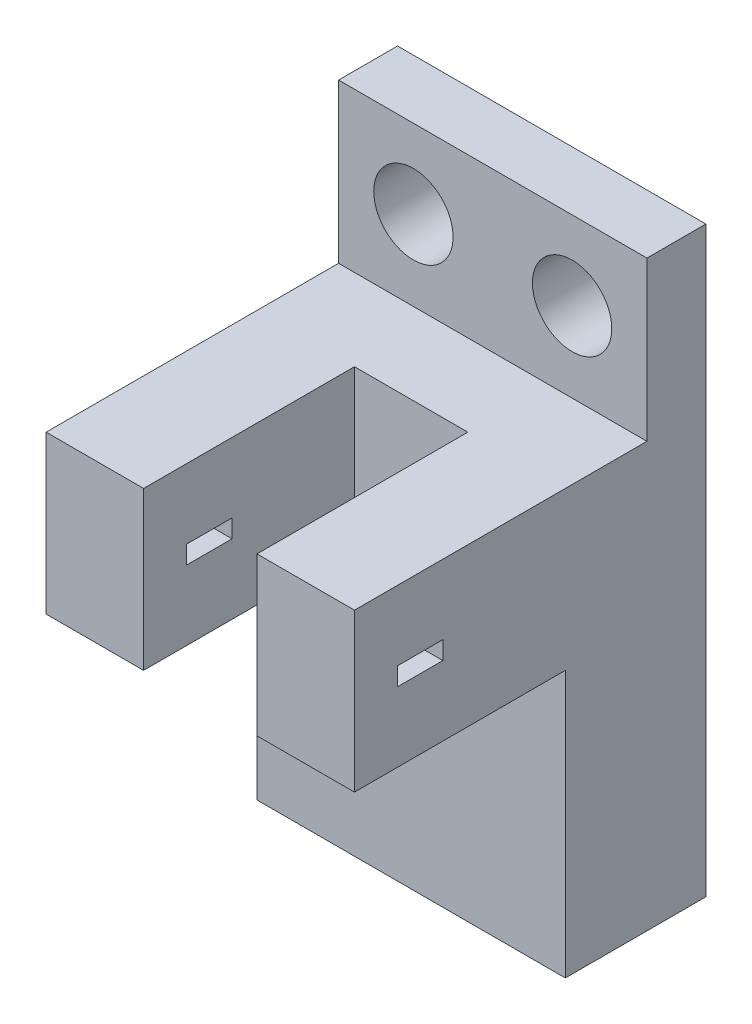
SolidWorks part; units mm, degrees
ref_plane "前视基准面" through (0, 0, 0) normal (0, 0, 1) x (1, 0, 0)
ref_plane "上视基准面" through (0, 0, 0) normal (0, 1, 0) x (1, 0, 0)
ref_plane "右视基准面" through (0, 0, 0) normal (1, 0, 0) x (0, 0, -1)
sketch "草图1" plane through (0, 0, 0) normal (0, 0, 1) x (1, 0, 0)
  line L1 (-6.8, -10.1) -> (6.8, -10.1)
  line L2 (-6.8, -10.1) -> (-6.8, 8.6)
  line L3 (-6.8, 8.6) -> (6.8, 8.6)
  line L4 (6.8, -10.1) -> (6.8, 8.6)
  line L5 (-6.8, -10.1) -> (6.8, 8.6) construction
  line L6 (-6.8, 8.6) -> (6.8, -10.1) construction
  point P0 (0, -0.75)
  dimension "D1" = 13.6
  dimension "D2" = 18.7
extrude "凸台-拉伸1" add sketch "草图1" along normal blind 6.2
sketch "草图2" plane through (0, 0, 6.2) normal (0, 0, 1) x (1, 0, 0)
  line L0 (2.5, 1.65) -> (6.8, 1.65)
  line L1 (-6.8, 1.65) -> (-2.5, 1.65)
  line L2 (-6.8, 1.65) -> (-6.8, 8.6)
  line L3 (-6.8, 8.6) -> (-2.5, 8.6)
  line L4 (-2.5, 1.65) -> (-2.5, 8.6)
  line L5 (-6.8, 1.65) -> (-2.5, 8.6) construction
  line L6 (-6.8, 8.6) -> (-2.5, 1.65) construction
  line L7 (2.5, 1.65) -> (2.5, 8.6)
  line L8 (2.5, 8.6) -> (6.8, 8.6)
  line L9 (6.8, 1.65) -> (6.8, 8.6)
  point P0 (-4.65, 5.125)
  dimension "D1" = 6.95
  dimension "D2" = 4.3
  dimension "D3" = 4.3
  dimension "D4" = 6.95
extrude "凸台-拉伸2" add sketch "草图2" along normal blind 9.3
sketch "草图3" plane through (0, 0, 0) normal (0, 0, -1) x (-1, 0, 0)
  line L0 (-3.5, 12.125) -> (3.5, 12.125) construction
  line L1 (-6.8, 15.6) -> (6.8, 15.6)
  line L2 (-6.8, 15.6) -> (-6.8, 8.6)
  line L3 (-6.8, 8.6) -> (6.8, 8.6)
  line L4 (6.8, 15.6) -> (6.8, 8.6)
  line L5 (-6.8, 15.6) -> (6.8, 8.6) construction
  line L6 (-6.8, 8.6) -> (6.8, 15.6) construction
  circle A0 centre (-3.5, 12.125) radius 1.75
  circle A1 centre (3.5, 12.125) radius 1.75
  point P0 (0, 12.1)
  point P12 (0, 12.125)
  dimension "D2" = 7
  dimension "D3" = 3.5
  dimension "D1" = 7
  dimension "D4" = 3.525
extrude "凸台-拉伸3" add sketch "草图3" against normal blind 2.6
sketch "草图4" plane through (6.8, 0, 0) normal (1, 0, 0) x (0, 0, -1)
  line L0 (-15.5, 1.65) -> (-15.5, 8.6) construction
  line L1 (-13.6, 4.725) -> (-11.6, 4.725)
  line L2 (-13.6, 4.725) -> (-13.6, 5.525)
  line L3 (-13.6, 5.525) -> (-11.6, 5.525)
  line L4 (-11.6, 4.725) -> (-11.6, 5.525)
  line L5 (-13.6, 4.725) -> (-11.6, 5.525) construction
  line L6 (-13.6, 5.525) -> (-11.6, 4.725) construction
  point P0 (-12.6, 5.125)
  point P8 (-15.5, 5.125)
  dimension "D1" = 0.8
  dimension "D2" = 2
  dimension "D3" = 2.9
extrude "切除-拉伸1" cut sketch "草图4" against normal through all
